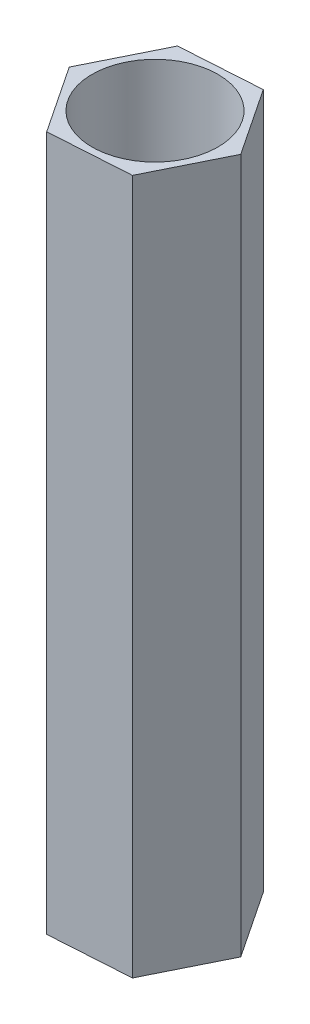
SolidWorks part; units mm, degrees
ref_plane "Front Plane" through (0, 0, 0) normal (0, 0, 1) x (1, 0, 0)
ref_plane "Top Plane" through (0, 0, 0) normal (0, 1, 0) x (1, 0, 0)
ref_plane "Right Plane" through (0, 0, 0) normal (1, 0, 0) x (0, 0, -1)
sketch "Sketch1" plane through (0, 0, 0) normal (0, 1, 0) x (1, 0, 0)
  line L1 (1.5988, -2.4036) -> (2.881, 0.1828)
  line L2 (2.881, 0.1828) -> (1.2822, 2.5864)
  line L3 (1.2822, 2.5864) -> (-1.5988, 2.4036)
  line L4 (-1.5988, 2.4036) -> (-2.881, -0.1828)
  line L5 (-2.881, -0.1828) -> (-1.2822, -2.5864)
  line L6 (-1.2822, -2.5864) -> (1.5988, -2.4036)
  circle A0 centre (0, 0) radius 2.5 construction
  circle A1 centre (0, 0) radius 2.25
  dimension "D1" = 5
  dimension "D2" = 4.5
extrude "Boss-Extrude1" add sketch "Sketch1" along normal blind 24.83
